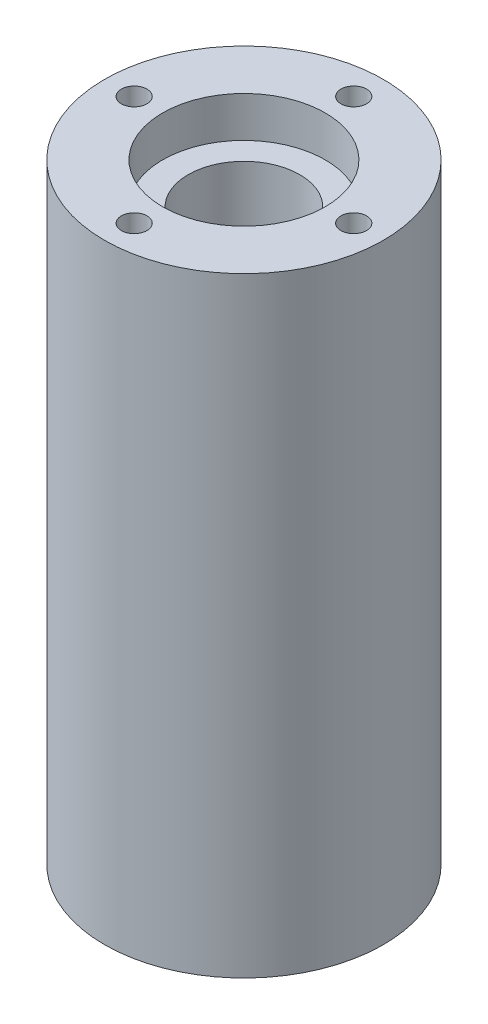
SolidWorks part; units mm, degrees
material "Alloy Steel (SS)"
ref_plane "Front Plane" through (0, 0, 0) normal (0, 0, 1) x (1, 0, 0)
ref_plane "Top Plane" through (0, 0, 0) normal (0, 1, 0) x (1, 0, 0)
ref_plane "Right Plane" through (0, 0, 0) normal (1, 0, 0) x (0, 0, -1)
sketch "Sketch1" plane through (0, 0, 0) normal (0, 1, 0) x (1, 0, 0)
  circle A0 centre (0, 0) radius 19.05
  circle A1 centre (0, 0) radius 7.62
  dimension "D1" = 38.1
  dimension "D2" = 15.24
extrude "Boss-Extrude1" add sketch "Sketch1" along normal blind 83.3482
sketch "Sketch3" plane through (0, 83.3482, 0) normal (0, 1, 0) x (1, 0, 0)
  circle A0 centre (0, 0) radius 11.1125
  dimension "D1" = 22.225
extrude "Cut-Extrude2" cut sketch "Sketch3" against normal blind 5.5563
sketch "Sketch4" plane through (0, 0, 0) normal (0, -1, 0) x (1, 0, 0)
  circle A0 centre (0, 0) radius 11.1125
  dimension "D1" = 22.225
extrude "Cut-Extrude3" cut sketch "Sketch4" against normal blind 5.5563
sketch "Sketch13" plane through (0, 83.3482, 0) normal (0, 1, 0) x (1, 0, 0)
  circle A0 centre (0, 15) radius 1.75
  dimension "D1" = 3.5
  dimension "D2" = 15
extrude "Cut-Extrude4" cut sketch "Sketch13" against normal blind 13
pattern_circular "CirPattern2" count 4 over 360 about axis through (0, 0, 0) along (0, 1, 0) of "Cut-Extrude4"
sketch "Sketch19" plane through (0, 0, 0) normal (0, -1, 0) x (1, 0, 0)
  circle A4 centre (0, 15) radius 1.75
  dimension "D1" = 3.5
  dimension "D2" = 15
extrude "Cut-Extrude6" cut sketch "Sketch19" against normal blind 13
pattern_circular "CirPattern4" count 4 over 360 about axis through (0, 0, 0) along (0, 1, 0) of "Cut-Extrude6"
